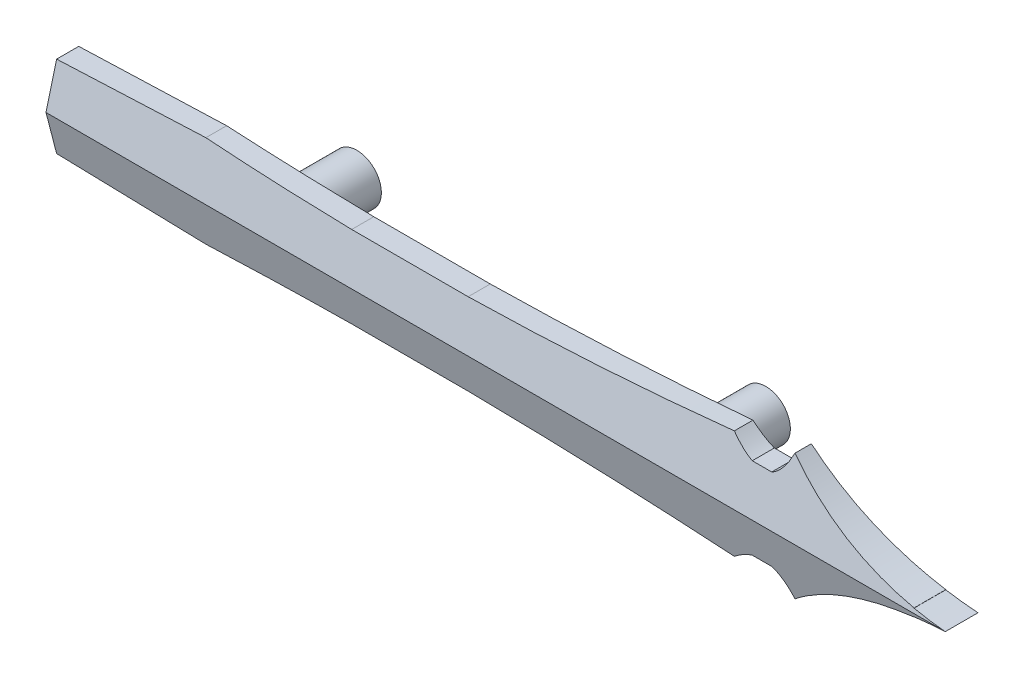
SolidWorks part; units mm, degrees
ref_plane "Ebene vorne" through (0, 0, 0) normal (0, 0, 1) x (1, 0, 0)
ref_plane "Ebene oben" through (0, 0, 0) normal (0, 1, 0) x (1, 0, 0)
ref_plane "Ebene rechts" through (0, 0, 0) normal (1, 0, 0) x (0, 0, -1)
sketch "Skizze1" plane through (0, 0, 0) normal (0, 0, 1) x (1, 0, 0)
  line L1 (0, 0) -> (53, 0)
  line L2 (0, 0) -> (0, 5)
  line L3 (0, 5) -> (53, 5)
  line L4 (53, 0) -> (53, 5)
  dimension "D1" = 53
  dimension "D2" = 5
extrude "Aufsatz-Linear austragen1" add sketch "Skizze1" along normal blind 2
sketch "Skizze2" plane through (0, 0, 0) normal (0, 0, -1) x (-1, 0, 0)
  line L0 (-53, 5) -> (0, 5) construction
  line L1 (-53, 0) -> (-53, 5) construction
  circle A0 centre (-38, 2.5) radius 1.5
  circle A1 centre (-13, 2.5) radius 1.5
  dimension "D1" = 2.5
  dimension "D2" = 2.5
  dimension "D3" = 25
  dimension "D4" = 15
  dimension "D5" = 3
  dimension "D6" = 3
extrude "Aufsatz-Linear austragen2" add sketch "Skizze2" along normal blind 4
sketch "Skizze3" plane through (0, 0, 2) normal (0, 0, 1) x (1, 0, 0)
  line L0 (54.9708, 2.5) -> (-1.9532, 2.5) construction
  line L1 (53, 5) -> (0, 5) construction
  line L2 (9.0417, 5.3198) -> (0, 5)
  line L3 (0, 5) -> (0, 0)
  line L4 (0, 5) -> (0, 0) construction
  line L5 (9.0417, -0.3198) -> (0, 0)
  spline S0 degree 2 poles (54.9708, 2.5) (49.1406, 2.9033) (44.783, 6.3561) knots 0 0 0 1 1 1
  spline S1 degree 2 poles (44.783, 6.3561) (43.7187, 3.6985) (41.2148, 5.8209) knots 0 0 0 1 1 1
  spline S2 degree 2 poles (41.2148, 5.8209) (25.1282, 4.4288) (9.0417, 5.3198) knots 0 0 0 1 1 1
  spline S3 degree 2 poles (54.9708, 2.5) (49.1406, 2.0967) (44.783, -1.3561) knots 0 0 0 1 1 1
  spline S4 degree 2 poles (44.783, -1.3561) (43.7187, 1.3015) (41.2148, -0.8209) knots 0 0 0 1 1 1
  spline S5 degree 2 poles (41.2148, -0.8209) (25.1282, 0.5712) (9.0417, -0.3198) knots 0 0 0 1 1 1
  point P16 (0, 2.5)
extrude "Aufsatz-Linear austragen3" add sketch "Skizze3" against normal blind 2
sketch "Skizze4" plane through (0, 0, 2) normal (0, 0, 1) x (1, 0, 0)
  line L0 (55.5749, 2.5) -> (42.6206, 2.5) construction
  line L1 (44.783, -1.3561) -> (55.5749, -1.3561)
  line L2 (55.5749, -1.3561) -> (55.5749, 6.3561)
  line L3 (55.5749, 6.3561) -> (44.783, 6.3561)
  spline S0 degree 2 poles (44.783, 6.3561) (48.81, 2.9927) (54.9708, 2.5) knots 0 0 0 1 1 1
  spline S1 degree 2 poles (44.783, -1.3561) (48.81, 2.0073) (54.9708, 2.5) knots 0 0 0 1 1 1
extrude "Schnitt-Linear austragen1" cut sketch "Skizze4" against normal blind 2
sketch "Skizze5" plane through (0, 0, 0) normal (-1, 0, 0) x (0, 0, 1)
  line L0 (1, 6.3561) -> (2, 2.5)
  line L1 (0, 6.3561) -> (2, 6.3561) construction
  line L2 (2, 5) -> (2, 0) construction
  line L3 (2, 2.5) -> (1, -1.3561)
  line L4 (0, -1.3561) -> (2, -1.3561) construction
  line L5 (1, -1.3561) -> (2.2378, -1.3561)
  line L6 (2.2378, -1.3561) -> (2.3197, 6.3561)
  line L7 (2.3197, 6.3561) -> (1, 6.3561)
extrude "Schnitt-Linear austragen2" cut sketch "Skizze5" against normal blind 62
